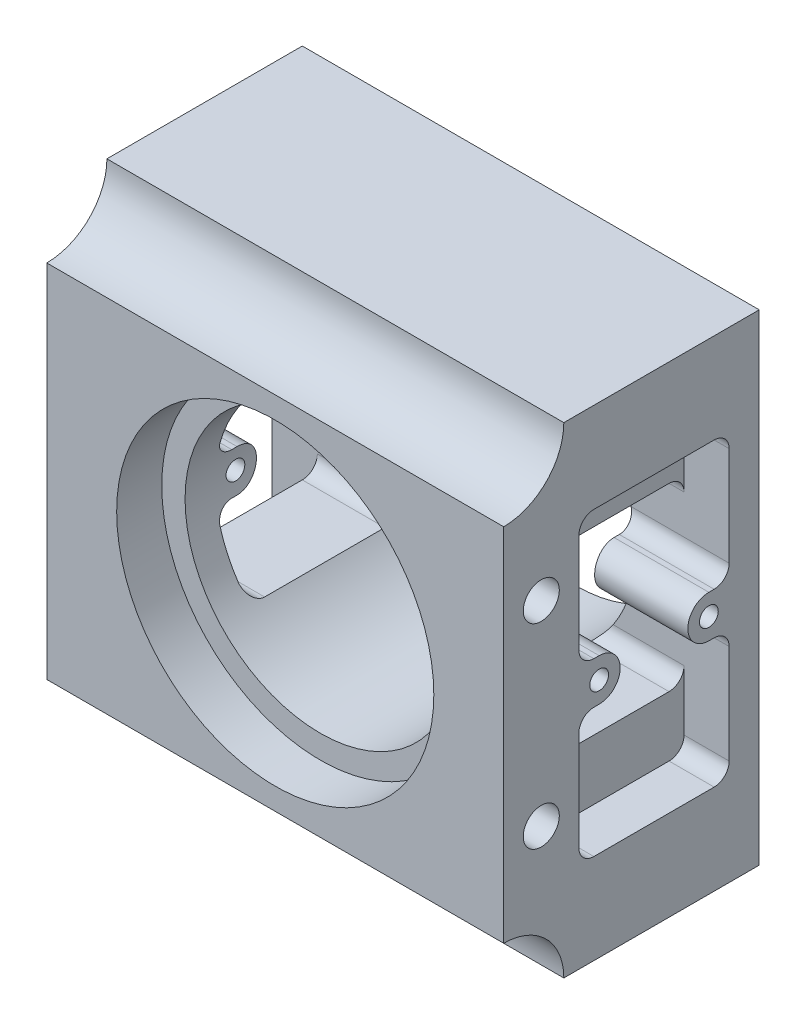
SolidWorks part; units mm, degrees
material "6061 合金"
ref_plane "Front" through (0, 0, 0) normal (0, 0, 1) x (1, 0, 0)
ref_plane "Top" through (0, 0, 0) normal (0, 1, 0) x (1, 0, 0)
ref_plane "Right" through (0, 0, 0) normal (1, 0, 0) x (0, 0, -1)
sketch "草图1" plane through (0, 0, 0) normal (0, 0, 1) x (1, 0, 0)
  line L1 (15.2, -16) -> (-15.2, -16)
  line L2 (15.2, -16) -> (15.2, 16)
  line L3 (15.2, 16) -> (-15.2, 16)
  line L4 (-15.2, -16) -> (-15.2, 16)
  line L5 (15.2, -16) -> (-15.2, 16) construction
  line L6 (15.2, 16) -> (-15.2, -16) construction
  point P0 (0, 0)
  dimension "D1" = 30.4
  dimension "D2" = 32
extrude "凸台-拉伸1" add sketch "草图1" along normal mid plane 20
sketch "草图2" plane through (0, 0, 10) normal (0, 0, 1) x (1, 0, 0)
  circle A0 centre (0, 0) radius 9
  dimension "D1" = 18
extrude "切除-拉伸1" cut sketch "草图2" against normal through all
sketch "草图3" plane through (0, 0, 10) normal (0, 0, 1) x (1, 0, 0)
  circle A0 centre (0, 0) radius 10.55
  dimension "D1" = 21.1
extrude "切除-拉伸2" cut sketch "草图3" against normal blind 3
sketch "草图4" plane through (15.2, 0, 0) normal (1, 0, 0) x (0, 0, -1)
  line L1 (2.25, -6) -> (-2.25, -6)
  line L2 (2.25, -6) -> (2.25, 6)
  line L3 (2.25, 6) -> (-2.25, 6)
  line L4 (-2.25, -6) -> (-2.25, 6)
  line L5 (2.25, -6) -> (-2.25, 6) construction
  line L6 (2.25, 6) -> (-2.25, -6) construction
  point P0 (0, 0)
  dimension "D1" = 4.5
  dimension "D2" = 12
extrude "切除-拉伸3" cut sketch "草图4" against normal through all
sketch "草图5" plane through (15.2, 0, 0) normal (1, 0, 0) x (0, 0, -1)
  line L0 (2.25, 6) -> (5, 6)
  line L1 (5, 6) -> (5, 1.4)
  line L2 (5, -6) -> (2.25, -6)
  line L3 (2.25, -6) -> (2.25, 6)
  line L4 (-2.25, 6) -> (-5, 6)
  line L5 (-5, 6) -> (-5, 1.4)
  line L6 (-5, -6) -> (-2.25, -6)
  line L7 (-2.25, -6) -> (-2.25, 6)
  line L8 (-3.65, 1.4) -> (-5, 1.4)
  line L9 (-3.65, -1.4) -> (-5, -1.4)
  line L10 (3.65, 1.4) -> (5, 1.4)
  line L11 (3.65, -1.4) -> (5, -1.4)
  line L12 (-5, -1.4) -> (-5, -6)
  line L13 (5, -1.4) -> (5, -6)
  arc A0 (3.65, 1.4) -> (3.65, -1.4) centre (3.65, 0) ccw
  arc A1 (-3.65, -1.4) -> (-3.65, 1.4) centre (-3.65, 0) ccw
  line M14 (-2.25, -6) -> (-2.25, 6)
  line M16 (2.25, 6) -> (2.25, -6)
  dimension "D1" = 5
  dimension "D2" = 5
  dimension "D3" = 3.65
  dimension "D4" = 3.65
extrude "切除-拉伸4" cut sketch "草图5" against normal through all contours A0 L10 L1 L0 M16 | A0 L3 L2 L13 L11 | A1 L9 L12 L6 M14 | A1 L7 L4 L5 L8
sketch "草图6" plane through (15.2, 0, 0) normal (1, 0, 0) x (0, 0, -1)
  point P0 (-3.65, 0)
  point P1 (3.65, 0)
hole_wizard "M1.6 螺纹孔1" positions "3D草图1" profile "草图7" tap size "M1.6" standard "GB" end condition through all
sketch3d "3D草图1"
  point P0 (15.2, 0, 3.65)
  point P3 (15.2, 0, -3.65)
sketch "草图7" plane through (15.2, 0, 3.65) normal (0, 1, 0) x (0, 0, -1)
  line L0 (0, 0) -> (0, 30.4)
  line L1 (0, 30.4) -> (0.625, 30.4)
  line L2 (0.625, 30.4) -> (0.625, 0)
  line L5 (0.625, 0) -> (0, 0)
  line L11 (0, -6.35) -> (0, 107.95) construction
  dimension "通孔螺纹孔钻头直径" = 1.25
  dimension "通孔螺纹孔钻头深度" = 30.4
cosmetic thread "孔螺蚊线1" parameters "D2"=1.6
cosmetic thread "孔螺蚊线2" parameters "D2"=1.6
sketch "草图8" plane through (15.2, 0, 0) normal (1, 0, 0) x (0, 0, -1)
  line L1 (5, 10) -> (-5, 10)
  line L2 (5, 10) -> (5, 6)
  line L3 (5, 6) -> (-5, 6)
  line L4 (-5, 10) -> (-5, 6)
  line L5 (5, 10) -> (-5, 6) construction
  line L6 (5, 6) -> (-5, 10) construction
  line L7 (5, -10) -> (-5, -10)
  line L8 (5, -10) -> (5, -6)
  line L9 (5, -6) -> (-5, -6)
  line L10 (-5, -10) -> (-5, -6)
  line L11 (5, -10) -> (-5, -6) construction
  line L12 (5, -6) -> (-5, -10) construction
  point P0 (0, 8)
  point P6 (0, -8)
  dimension "D1" = 10
  dimension "D2" = 10
extrude "切除-拉伸5" cut sketch "草图8" against normal blind 3
sketch "草图9" plane through (-15.2, 0, 0) normal (-1, 0, 0) x (0, 0, 1)
  line L0 (5, -6) -> (5, -10) construction
  line L1 (5, -10) -> (-5, -10) construction
  line L2 (-5, -10) -> (-5, -6) construction
  line L3 (-5, -6) -> (5, -6) construction
  line L4 (5, 10) -> (5, 6) construction
  line L5 (5, 6) -> (-5, 6) construction
  line L6 (-5, 6) -> (-5, 10) construction
  line L7 (-5, 10) -> (5, 10) construction
  line L8 (5, -6) -> (5, -10)
  line L9 (5, -10) -> (-5, -10)
  line L10 (-5, -10) -> (-5, -6)
  line L11 (-5, -6) -> (5, -6)
  line L12 (5, 10) -> (5, 6)
  line L13 (5, 6) -> (-5, 6)
  line L14 (-5, 6) -> (-5, 10)
  line L15 (-5, 10) -> (5, 10)
extrude "切除-拉伸6" cut sketch "草图9" against normal blind 3
fillet "圆角1" radius 1 24 edges at (9.4541, 6, -5) (13.7, 10, -5) (13.7, -10, -5) (9.4541, -6, -5) (13.7, -10, 5) (9.4541, -6, 5) (13.7, 10, 5) (9.4541, 6, 5) (12.0452, -1.4, 5) (12.0452, 1.4, 5) (12.0452, 1.4, -5) (12.0452, -1.4, -5) (-9.4541, 6, -5) (-9.4541, 6, 5) (-9.4541, -6, 5) (-9.4541, -6, -5) (-13.7, -10, 5) (-13.7, -10, -5) (-13.7, 10, -5) (-13.7, 10, 5) (-12.0452, 1.4, 5) (-12.0452, -1.4, 5) (-12.0452, -1.4, -5) (-12.0452, 1.4, -5)
sketch "草图10" plane through (0, 0, -10) normal (0, 0, -1) x (-1, 0, 0)
  line L4 (15.2, -16) -> (15.2, 16)
  line L5 (15.2, 16) -> (-15.2, 16)
  line L6 (-15.2, 16) -> (-15.2, -16)
  line L7 (-15.2, -16) -> (15.2, -16)
  line L8 (15.2, -16) -> (15.2, 16)
  line L9 (15.2, 16) -> (-15.2, 16)
  line L10 (-15.2, 16) -> (-15.2, -16)
  line L11 (-15.2, -16) -> (15.2, -16)
  circle A0 centre (0, 0) radius 10.5
  dimension "D2" = 21
  dimension "D1" = 0
extrude "切除-拉伸7" cut sketch "草图10" against normal blind 3
sketch "草图11" plane through (0, -16, 0) normal (0, -1, 0) x (1, 0, 0)
  line L0 (-15.2, 10) -> (15.2, 10) construction
  point P0 (-8, 2)
  point P1 (8, 2)
  dimension "D1" = 8
  dimension "D2" = 8
  dimension "D3" = 8
hole_wizard "M3 螺纹孔1" positions "3D草图2" profile "草图12" tap size "M3" standard "GB"
sketch3d "3D草图2"
  point P0 (-8, -16, 2)
  point P3 (8, -16, 2)
sketch "草图12" plane through (-8, -16, 2) normal (1, 0, 0) x (0, 0, -1)
  line L0 (0, 0) -> (0, 7.2511)
  line L1 (0, 7.2511) -> (1.25, 6.5)
  line L2 (1.25, 6.5) -> (1.25, 0)
  line L5 (1.25, 0) -> (0, 0)
  line L10 (0, 7.2511) -> (-1.25, 6.5) construction
  line L11 (0, -6.35) -> (0, 107.95) construction
  dimension "螺纹孔钻头直径" = 2.5
  dimension "螺纹孔钻头深度" = 6.5
  dimension "导头角度" = 118
cosmetic thread "孔螺蚊线3" parameters "D1"=4, "D2"=3
cosmetic thread "孔螺蚊线4" parameters "D1"=4, "D2"=3
sketch "草图13" plane through (0, 0, -7) normal (0, 0, -1) x (-1, 0, 0)
  point P0 (-13, 13)
  point P1 (13, 13)
  point P2 (-13, -13)
  point P3 (13, -13)
  dimension "D1" = 13
  dimension "D2" = 13
  dimension "D3" = 13
  dimension "D4" = 13
hole_wizard "M3 螺纹孔2" positions "3D草图3" profile "草图14" tap size "M3" standard "GB"
sketch3d "3D草图3"
  point P0 (13, 13, -7)
  point P3 (-13, 13, -7)
  point P6 (-13, -13, -7)
  point P9 (13, -13, -7)
sketch "草图14" plane through (13, 13, -7) normal (1, 0, 0) x (0, 1, 0)
  line L0 (0, 0) -> (0, 5.2511)
  line L1 (0, 5.2511) -> (1.25, 4.5)
  line L2 (1.25, 4.5) -> (1.25, 0)
  line L5 (1.25, 0) -> (0, 0)
  line L10 (0, 5.2511) -> (-1.25, 4.5) construction
  line L11 (0, -6.35) -> (0, 107.95) construction
  dimension "螺纹孔钻头直径" = 2.5
  dimension "螺纹孔钻头深度" = 4.5
  dimension "导头角度" = 118
cosmetic thread "孔螺蚊线5" parameters "D1"=3, "D2"=3
cosmetic thread "孔螺蚊线6" parameters "D1"=3, "D2"=3
cosmetic thread "孔螺蚊线7" parameters "D1"=3, "D2"=3
cosmetic thread "孔螺蚊线8" parameters "D1"=3, "D2"=3
sketch "草图16" plane through (15.2, 0, 0) normal (1, 0, 0) x (0, 0, -1)
  circle A0 centre (-10, -16) radius 4
  circle A1 centre (-10, 16) radius 4
  dimension "D1" = 8
extrude "切除-拉伸8" cut sketch "草图16" against normal through all
sketch "草图17" plane through (15.2, 0, 0) normal (1, 0, 0) x (0, 0, -1)
  line L0 (-10, 0) -> (-7.5, 0) construction
  line L1 (-10, -12) -> (-10, 12) construction
  line L2 (-7.5, 0) -> (-7.5, -6.5) construction
  line L3 (-7.5, 0) -> (-7.5, 6.5) construction
  circle A0 centre (-7.5, -6.5) radius 1.2
  circle A1 centre (-7.5, 6.5) radius 1.2
  dimension "D1" = 2.4
  dimension "D2" = 2.4
  dimension "D3" = 2.5
  dimension "D4" = 6.5
extrude "切除-拉伸9" cut sketch "草图17" against normal blind 5
cosmetic thread "装饰螺纹线1" parameters "D2"=3
cosmetic thread "装饰螺纹线2" parameters "D2"=3
